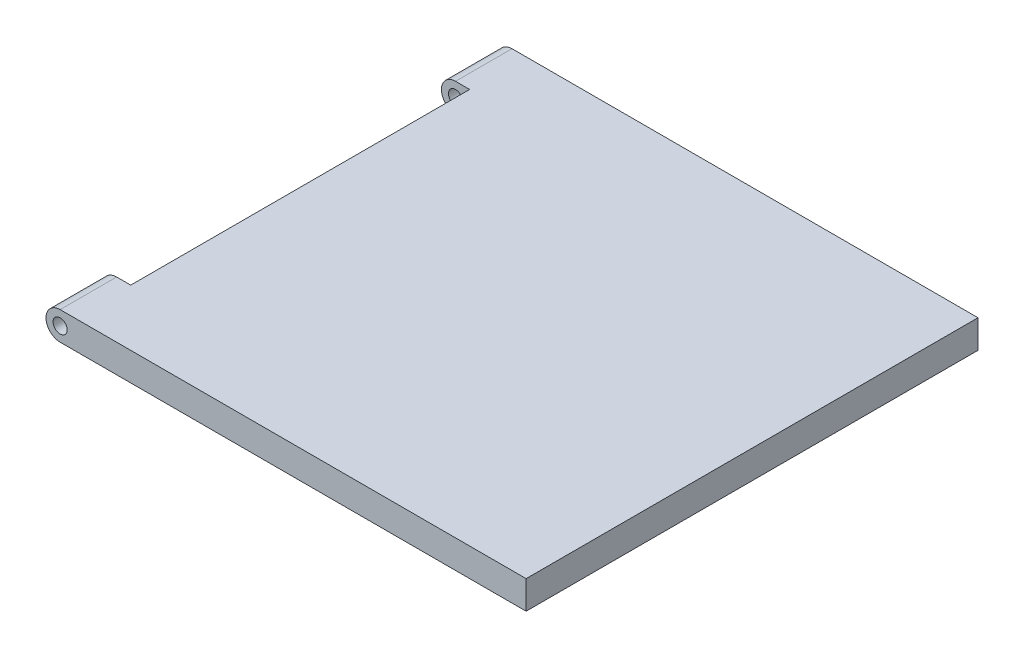
SolidWorks part; units mm, degrees
ref_plane "Front Plane" through (0, 0, 0) normal (0, 0, 1) x (1, 0, 0)
ref_plane "Top Plane" through (0, 0, 0) normal (0, 1, 0) x (1, 0, 0)
ref_plane "Right Plane" through (0, 0, 0) normal (1, 0, 0) x (0, 0, -1)
sketch "Sketch1" plane through (0, 0, 0) normal (0, 0, 1) x (1, 0, 0)
  line L0 (0, 0) -> (80, 0)
  line L1 (80, 0) -> (80, 10)
  line L2 (80, 10) -> (75, 10)
  line L3 (75, 10) -> (75, 5)
  line L4 (75, 5) -> (0, 5)
  line L5 (0, 5) -> (0, 0)
  dimension "D1" = 80
  dimension "D2" = 5
  dimension "D3" = 5
  dimension "D4" = 10
extrude "Boss-Extrude1" add sketch "Sketch1" along normal mid plane 80
sketch "Sketch2" plane through (0, 0, 0) normal (0, 0, 1) x (1, 0, 0)
  line L0 (0, 5) -> (-2.5, 5)
  line L1 (-2.5, 0) -> (0, 0)
  line L2 (0, 0) -> (0, 5)
  arc A0 (-2.5, 5) -> (-2.5, 0) centre (-2.5, 2.5) ccw
  circle A1 centre (-2.5, 2.5) radius 1.25
  dimension "D1" = 2.5
  dimension "D2" = 2.5
extrude "Boss-Extrude2" add sketch "Sketch2" along normal blind 10 from offset 30
mirror "Mirror2" about plane through (0, 0, 0) normal (0, 0, 1) of "Boss-Extrude2"
sketch "Sketch3" plane through (0, 0, 0) normal (0, 0, 1) x (1, 0, 0)
  line L0 (80, 0) -> (80, 10) construction
  line L1 (75, 10) -> (80, 10)
  line L2 (75, 10) -> (75, 5)
  line L3 (75, 5) -> (80, 5)
  line L4 (80, 10) -> (80, 5)
  dimension "D1" = 5
extrude "Cut-Extrude1" cut sketch "Sketch3" against normal through all both and the other way through all
